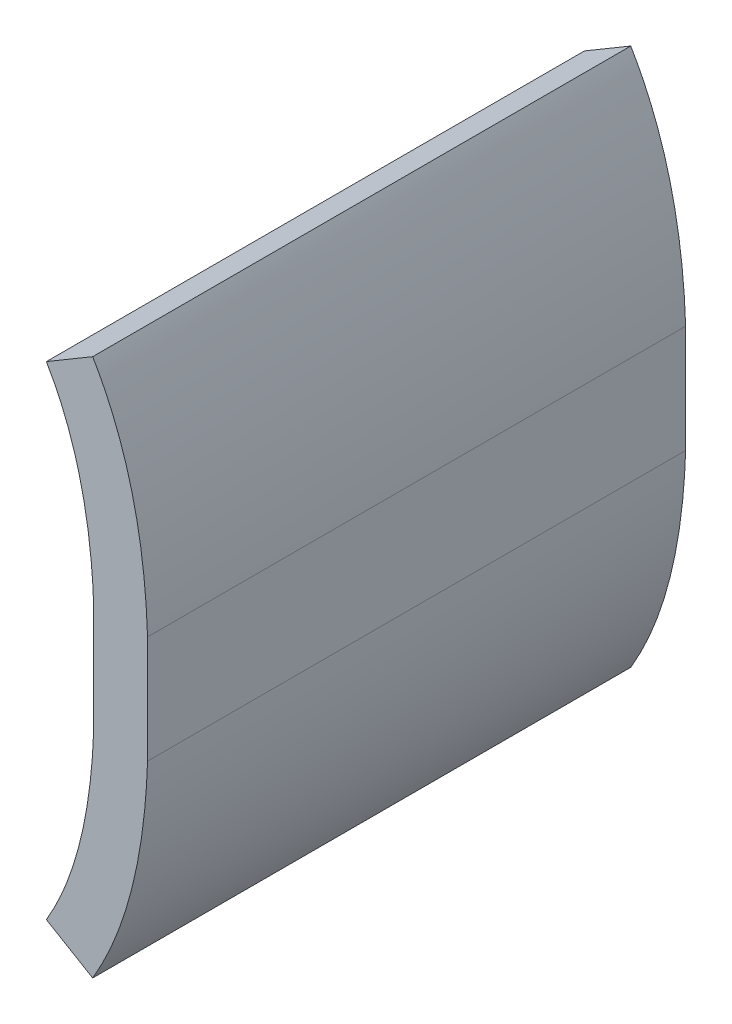
SolidWorks part; units mm, degrees
ref_plane "Front Plane" through (0, 0, 0) normal (0, 0, 1) x (1, 0, 0)
ref_plane "Top Plane" through (0, 0, 0) normal (0, 1, 0) x (1, 0, 0)
ref_plane "Right Plane" through (0, 0, 0) normal (1, 0, 0) x (0, 0, -1)
sketch "Sketch1" plane through (0, 0, 0) normal (0, 0, 1) x (1, 0, 0)
  line L0 (0, 0) -> (0, 10)
  line L1 (0, 0) -> (0, -10)
  line L2 (13.7971, 0) -> (-27.4718, 0) construction
  line L3 (-10, 0) -> (-10, -9.8335)
  line L4 (-10, 0) -> (-10, 9.8335)
  line L5 (-18.8032, 44.9066) -> (-10.1975, 50)
  line L6 (-10.1975, -50) -> (-18.8032, -44.9066)
  spline S0 degree 2 poles (0, 10) (-0.7872, 34.1007) (-10.1975, 50) knots 0 0 0 1 1 1
  spline S1 degree 2 poles (0, -10) (-0.7872, -34.1007) (-10.1975, -50) knots 0 0 0 1 1 1
  spline S2 degree 1 poles (-10, -9.8335) (-18.8032, -44.9066) knots 0 0 1 1 construction
  spline S3 degree 1 poles (-10, 9.8335) (-18.8032, 44.9066) knots 0 0 1 1 construction
  spline S4 degree 3 poles (-18.8032, -44.9066) (-18.1443, -43.7934) (-16.9287, -41.5442) (-14.7288, -36.6349) (-12.9497, -31.1969) (-11.6034, -25.176) (-10.8203, -20.372) (-10.3615, -16.1193) (-10.1147, -12.5827) (-10.031, -10.7445) (-10, -9.8335) knots 0.003595 0.003595 0.003595 0.003595 0.128146 0.252697 0.501798 0.626348 0.750899 0.875449 0.937725 1 1 1 1
  spline S5 degree 3 poles (-10, 9.8335) (-10.031, 10.7445) (-10.1147, 12.5827) (-10.3615, 16.1193) (-10.8203, 20.372) (-11.6034, 25.176) (-12.9497, 31.1969) (-14.7288, 36.6349) (-16.9287, 41.5442) (-18.1443, 43.7934) (-18.8032, 44.9066) knots 0.003595 0.003595 0.003595 0.003595 0.065871 0.128146 0.252697 0.377247 0.501798 0.750899 0.875449 1 1 1 1
  dimension "D1" = 10
  dimension "D2" = 10
  dimension "D3" = 50
  dimension "D4" = 10
extrude "Boss-Extrude1" add sketch "Sketch1" along normal blind 100
